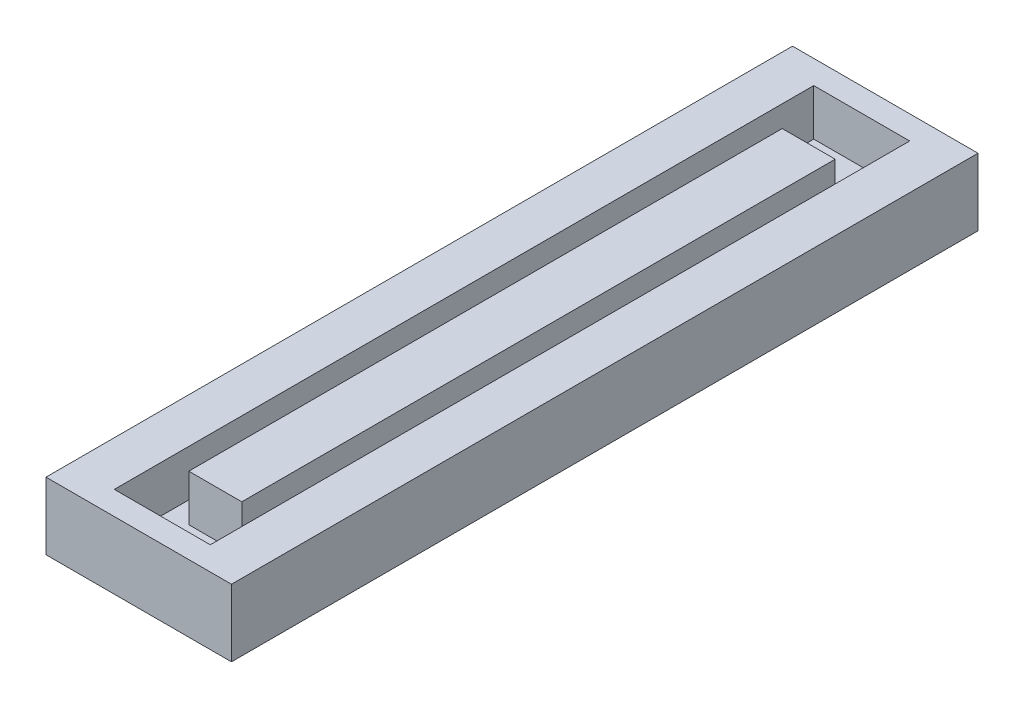
SolidWorks part; units mm, degrees
ref_plane "Front Plane" through (0, 0, 0) normal (0, 0, 1) x (1, 0, 0)
ref_plane "Top Plane" through (0, 0, 0) normal (0, 1, 0) x (1, 0, 0)
ref_plane "Right Plane" through (0, 0, 0) normal (1, 0, 0) x (0, 0, -1)
ref_plane "Plane1" through (0, 1.45, 0) normal (0, 1, 0) x (-1, 0, 0)
sketch "Sketch1" plane through (0, 1.45, 0) normal (0, 1, 0) x (-1, 0, 0)
  line L0 (-2, -8.05) -> (2, -8.05)
  line L1 (2, -8.05) -> (2, 8.05)
  line L2 (2, 8.05) -> (-2, 8.05)
  line L3 (-2, 8.05) -> (-2, -8.05)
extrude "Boss-Extrude1" add sketch "Sketch1" against normal blind 1.45
sketch "Sketch2" plane through (0, 1.45, 0) normal (0, 1, 0) x (-1, 0, 0)
  line L0 (-1.0348, -7.542) -> (1.0348, -7.542)
  line L1 (1.0348, -7.542) -> (1.0348, 7.542)
  line L2 (1.0348, 7.542) -> (-1.0348, 7.542)
  line L3 (-1.0348, 7.542) -> (-1.0348, -7.542)
extrude "Cut-Extrude1" cut sketch "Sketch2" against normal blind 1
sketch "Sketch3" plane through (0, 0.45, 0) normal (0, 1, 0) x (-1, 0, 0)
  line L0 (0.5715, -6.399) -> (-0.5715, -6.399)
  line L1 (-0.5715, -6.399) -> (-0.5715, 6.399)
  line L2 (-0.5715, 6.399) -> (0.5715, 6.399)
  line L3 (0.5715, 6.399) -> (0.5715, -6.399)
extrude "Boss-Extrude2" add sketch "Sketch3" along normal blind 1
